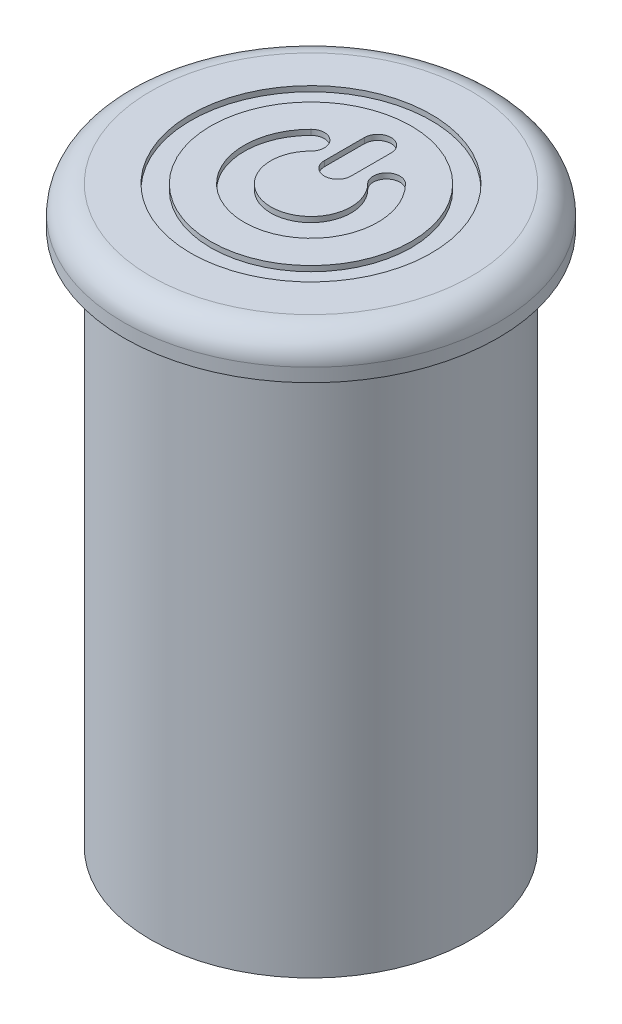
SolidWorks part; units mm, degrees
ref_plane "前视基准面" through (0, 0, 0) normal (0, 0, 1) x (1, 0, 0)
ref_plane "上视基准面" through (0, 0, 0) normal (0, 1, 0) x (1, 0, 0)
ref_plane "右视基准面" through (0, 0, 0) normal (1, 0, 0) x (0, 0, -1)
sketch "草图1" plane through (0, 0, 0) normal (0, 0, 1) x (1, 0, 0)
  line L0 (0, 0) -> (7, 0)
  line L1 (7, 0) -> (7, -1.5)
  line L2 (7, -1.5) -> (6, -1.5)
  line L3 (6, -1.5) -> (6, -21.5)
  line L4 (6, -21.5) -> (0, -21.5)
  line L5 (0, -21.5) -> (0, 0)
  line L6 (0, 0) -> (0, 3.583) construction
  dimension "D1" = 14
  dimension "D2" = 12
  dimension "D3" = 1.5
  dimension "D4" = 20
revolve "旋转1" add sketch "草图1" angle 360 about L6
fillet "圆角1" radius 1 1 edges at (0, 0, -7)
sketch "草图2" plane through (0, 0, 0) normal (0, 1, 0) x (1, 0, 0)
  line L0 (-1.4142, 1.4142) -> (0, 0) construction
  line L1 (0, 0) -> (1.4142, 1.4142) construction
  line L2 (0, 0) -> (0, 1) construction
  line L3 (0, 2.5) -> (0, 1) construction
  line L4 (0.5, 2.5) -> (0.5, 1)
  line L5 (-0.5, 2.5) -> (-0.5, 1)
  circle A0 centre (0, 0) radius 4.5
  circle A1 centre (0, 0) radius 3.75
  arc A2 (1.4142, 1.4142) -> (-1.4142, 1.4142) centre (0, 0) cw construction
  arc A3 (-1.7678, 1.7678) -> (1.7678, 1.7678) centre (0, 0) ccw
  arc A4 (-1.0607, 1.0607) -> (1.0607, 1.0607) centre (0, 0) ccw
  arc A5 (-1.0607, 1.0607) -> (-1.7678, 1.7678) centre (-1.4142, 1.4142) ccw
  arc A6 (1.7678, 1.7678) -> (1.0607, 1.0607) centre (1.4142, 1.4142) ccw
  arc A7 (0.5, 2.5) -> (-0.5, 2.5) centre (0, 2.5) ccw
  arc A8 (-0.5, 1) -> (0.5, 1) centre (0, 1) ccw
  point P7 (0, -2)
  point P16 (0, 1.75)
  dimension "D1" = 9
  dimension "D2" = 7.5
  dimension "D5" = 1
  dimension "D6" = 2.5
  dimension "D3" = 45
  dimension "D4" = 45
  dimension "D7" = 1
  dimension "D8" = 1.5
extrude "切除-拉伸1" cut sketch "草图2" against normal blind 0.2 contours L5 A8 L4 A7 | A3 A6 A4 A5 | A0 A1
